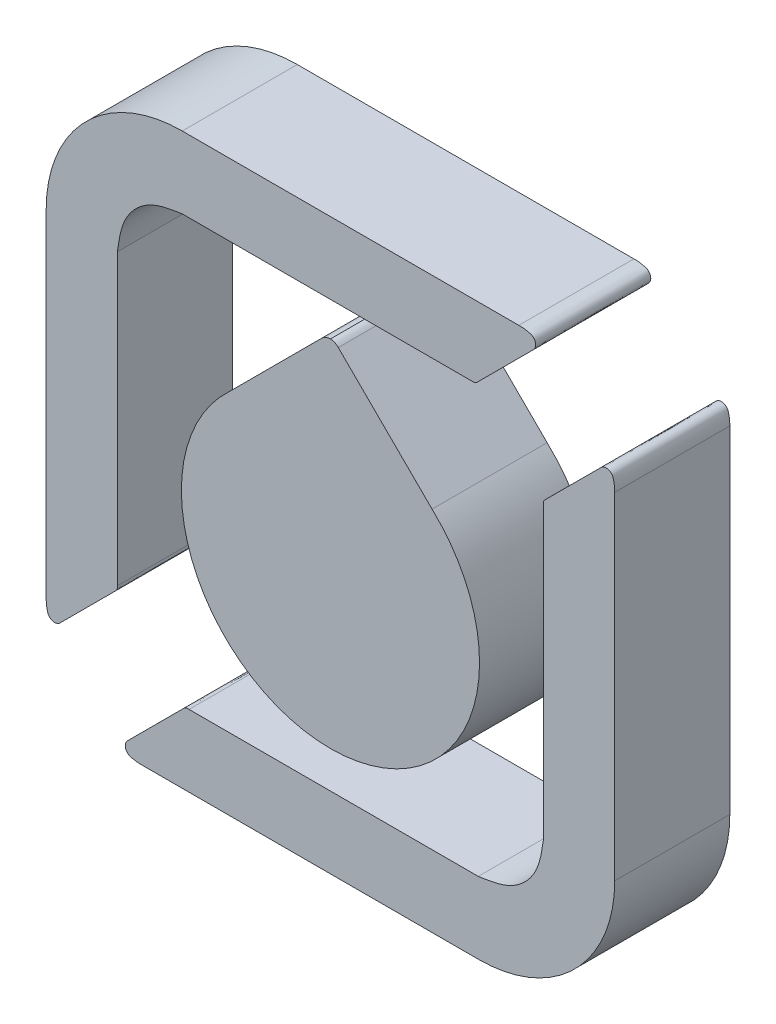
SolidWorks part; units mm, degrees
ref_plane "Front Plane" through (0, 0, 0) normal (0, 0, 1) x (1, 0, 0)
ref_plane "Top Plane" through (0, 0, 0) normal (0, 1, 0) x (1, 0, 0)
ref_plane "Right Plane" through (0, 0, 0) normal (1, 0, 0) x (0, 0, -1)
sketch "Sketch2" plane through (0, 0, 0) normal (0, 0, 1) x (1, 0, 0)
  line L0 (0, 45.4446) -> (0, 35.756) construction
  line L1 (0, 45.4446) -> (11.114, 45.4446) construction
  line L2 (0, 45.4446) -> (-11.114, 45.4446) construction
  line L3 (11.114, 45.4446) -> (14.8194, 45.4446) construction
  line L4 (-11.114, 45.4446) -> (-14.8194, 45.4446) construction
  line L5 (0, 35.756) -> (0, 32.0149) construction
  line L6 (0, 45.4446) -> (0, 57.9512) construction
  line L7 (-0.4438, 55.9843) -> (-5.2972, 51.1311)
  line L8 (5.2972, 51.1311) -> (0.4078, 55.9843)
  line L9 (-7.7062, 57.9512) -> (7.3729, 57.9512)
  line L10 (7.6431, 58.0344) -> (10.5964, 60.9874)
  line L11 (9.8185, 61.6923) -> (-7.7278, 61.6923)
  line L12 (-14.8194, 54.6007) -> (-14.8194, 37.0557)
  line L13 (-14.1152, 36.2786) -> (-11.198, 39.1954)
  line L14 (-11.114, 39.4645) -> (-11.114, 54.5429)
  line L15 (7.7061, 35.756) -> (-7.3717, 35.756)
  line L16 (-7.6423, 35.6721) -> (-10.5957, 32.7191)
  line L17 (-9.8171, 32.0149) -> (7.7257, 32.0149)
  line L18 (14.8194, 39.1086) -> (14.8194, 56.65)
  line L19 (14.1152, 57.4272) -> (11.1984, 54.5107)
  line L20 (11.114, 54.2423) -> (11.114, 39.1641)
  line L21 (0, 57.9512) -> (0, 61.6923) construction
  arc A0 (-5.2972, 51.1311) -> (5.2972, 51.1311) centre (0, 45.4446) ccw
  arc A3 (-7.7278, 61.6923) -> (-14.8194, 54.6007) centre (-7.7278, 54.6007) ccw
  arc A4 (7.7257, 32.0149) -> (14.8194, 39.1086) centre (7.7257, 39.1086) ccw
  spline S0 degree 3 poles (0.0001, 56.1691) (-0.0526, 56.164) (-0.161, 56.1535) (-0.3152, 56.0897) (-0.4012, 56.0192) (-0.4438, 55.9843) knots 0 0 0 0 0.322338 0.663828 1 1 1 1
  spline S2 degree 3 poles (0.4078, 55.9843) (0.3687, 56.0182) (0.2913, 56.0851) (0.1516, 56.1544) (0.0505, 56.1642) (0.0001, 56.1691) knots 0 0 0 0 0.338885 0.669777 1 1 1 1
  spline S3 degree 3 poles (7.3729, 57.9512) (7.3951, 57.9507) (7.4386, 57.9495) (7.5042, 57.9506) (7.5558, 57.9715) (7.5941, 57.9933) (7.6197, 58.0142) (7.6354, 58.0278) (7.6431, 58.0344) knots 0 0 0 0 0.227493 0.445972 0.663373 0.787115 0.896006 1 1 1 1
  spline S4 degree 3 poles (10.5964, 60.9874) (10.6255, 61.0267) (10.6835, 61.1053) (10.7077, 61.2534) (10.6806, 61.3894) (10.6134, 61.499) (10.523, 61.578) (10.3901, 61.6275) (10.23, 61.6599) (10.0449, 61.6934) (9.9145, 61.6909) (9.8432, 61.6925) (9.8308, 61.6932) (9.8226, 61.6926) (9.8185, 61.6923) knots 0 0 0 0 0.104345 0.208931 0.313565 0.397995 0.482811 0.567894 0.701187 0.836715 0.973247 0.982163 0.991064 1 1 1 1
  spline S6 degree 3 poles (-14.8194, 37.0557) (-14.8197, 37.0517) (-14.8203, 37.0438) (-14.8196, 37.0319) (-14.8181, 36.9607) (-14.8211, 36.8302) (-14.7873, 36.6447) (-14.7575, 36.4838) (-14.706, 36.3517) (-14.6274, 36.2614) (-14.5182, 36.1934) (-14.3819, 36.1662) (-14.2334, 36.1905) (-14.1546, 36.2492) (-14.1152, 36.2786) knots 0 0 0 0 0.008622 0.017031 0.025643 0.162638 0.298245 0.431901 0.516392 0.601007 0.685957 0.790142 0.895037 1 1 1 1
  spline S7 degree 3 poles (-11.198, 39.1954) (-11.1901, 39.2056) (-11.1745, 39.2255) (-11.1503, 39.2552) (-11.1254, 39.2935) (-11.1107, 39.3444) (-11.1073, 39.4043) (-11.1117, 39.4439) (-11.114, 39.4645) knots 0 0 0 0 0.131285 0.25763 0.390972 0.594165 0.788898 1 1 1 1
  spline S8 degree 3 poles (-11.114, 54.5429) (-11.0258, 55.1469) (-10.8533, 56.3272) (-9.4913, 57.6903) (-8.3106, 57.8629) (-7.7062, 57.9512) knots 0 0 0 0 0.33841 0.661392 1 1 1 1
  spline S9 degree 3 poles (-7.3717, 35.756) (-7.3908, 35.7572) (-7.4259, 35.7596) (-7.4804, 35.7568) (-7.5266, 35.7411) (-7.5688, 35.7217) (-7.6058, 35.6994) (-7.6298, 35.6815) (-7.6423, 35.6721) knots 0 0 0 0 0.196746 0.361608 0.557262 0.692766 0.839563 1 1 1 1
  spline S10 degree 3 poles (-10.5957, 32.7191) (-10.6247, 32.6798) (-10.6827, 32.6011) (-10.7067, 32.4529) (-10.6795, 32.3169) (-10.6119, 32.2075) (-10.5215, 32.1288) (-10.389, 32.0789) (-10.2289, 32.0463) (-10.0439, 32.0161) (-9.9133, 32.0106) (-9.842, 32.0158) (-9.8295, 32.0151) (-9.8212, 32.015) (-9.8171, 32.0149) knots 0 0 0 0 0.104385 0.20895 0.313569 0.398093 0.483012 0.567612 0.700915 0.836485 0.973043 0.982112 0.991066 1 1 1 1
  spline S12 degree 3 poles (14.8194, 56.65) (14.8197, 56.6541) (14.8203, 56.6624) (14.8196, 56.6749) (14.8182, 56.7463) (14.8207, 56.8767) (14.7873, 57.0618) (14.7555, 57.2218) (14.7055, 57.3543) (14.6269, 57.4448) (14.5175, 57.5124) (14.3814, 57.5396) (14.233, 57.5152) (14.1545, 57.4565) (14.1152, 57.4272) knots 0 0 0 0 0.008953 0.017947 0.027021 0.163491 0.298949 0.432165 0.516776 0.601601 0.686035 0.790672 0.895263 1 1 1 1
  spline S13 degree 3 poles (11.1984, 54.5107) (11.1897, 54.5006) (11.1727, 54.4807) (11.147, 54.4503) (11.1199, 54.4142) (11.108, 54.3634) (11.1091, 54.3046) (11.1123, 54.2639) (11.114, 54.2423) knots 0 0 0 0 0.134582 0.264928 0.404991 0.586048 0.77989 1 1 1 1
  spline S14 degree 3 poles (11.114, 39.1641) (11.0261, 38.56) (10.8542, 37.3794) (9.4914, 36.0167) (8.3105, 35.8443) (7.7061, 35.756) knots 0 0 0 0 0.338406 0.661372 1 1 1 1
  point P4 (13.0016, 34.3667)
  point P10 (-12.8822, 59.4713)
extrude "Boss-Extrude1" add sketch "Sketch2" along normal blind 6
